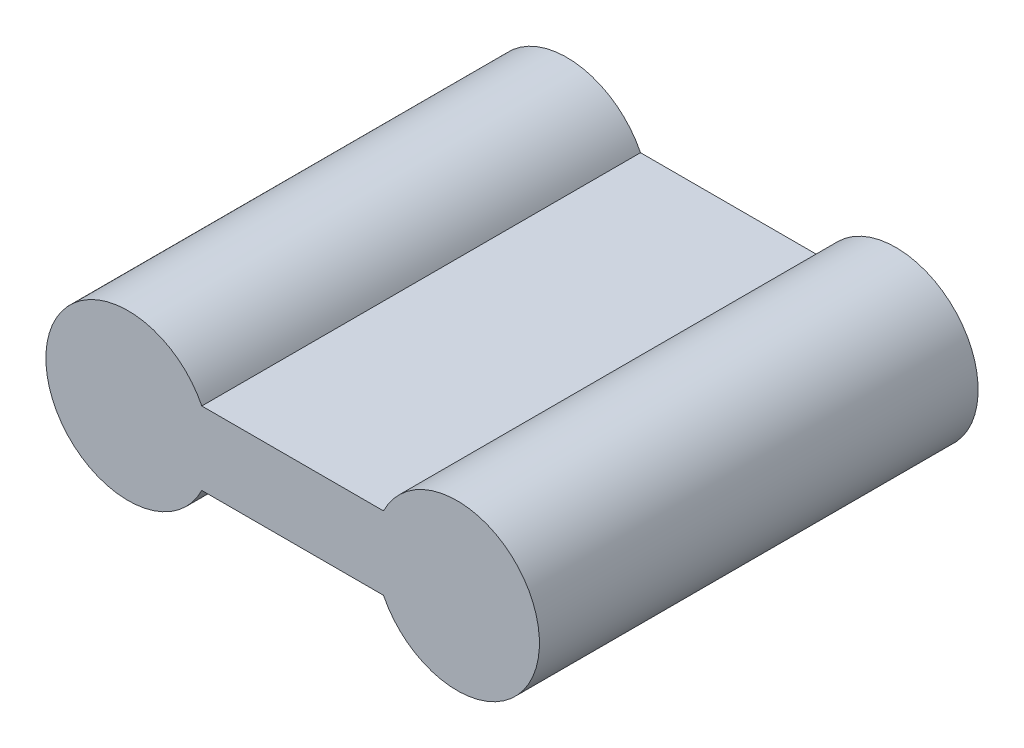
SolidWorks part; units mm, degrees
ref_plane "Front Plane" through (0, 0, 0) normal (0, 0, 1) x (1, 0, 0)
ref_plane "Top Plane" through (0, 0, 0) normal (0, 1, 0) x (1, 0, 0)
ref_plane "Right Plane" through (0, 0, 0) normal (1, 0, 0) x (0, 0, -1)
sketch "Sketch1" plane through (0, 0, 0) normal (0, 0, 1) x (1, 0, 0)
  line L1 (2.0156, 1) -> (6.9844, 1)
  line L3 (2.0156, -1) -> (6.9844, -1)
  line L5 (0.5933, 1) -> (8.3406, -1) construction
  line L6 (0.5933, -1) -> (8.3406, 1) construction
  arc A0 (2.0156, 1) -> (2.0156, -1) centre (0, 0) ccw
  arc A1 (6.9844, -1) -> (6.9844, 1) centre (9, 0) ccw
  point P11 (4.467, 0)
  dimension "D1" = 4.5
  dimension "D2" = 9
  dimension "D3" = 2
  dimension "D4" = 1
extrude "Boss-Extrude1" add sketch "Sketch1" along normal blind 12
ref_plane "Plane1" through (0, 0, 6) normal (0, 0, 1) x (1, 0, 0)
